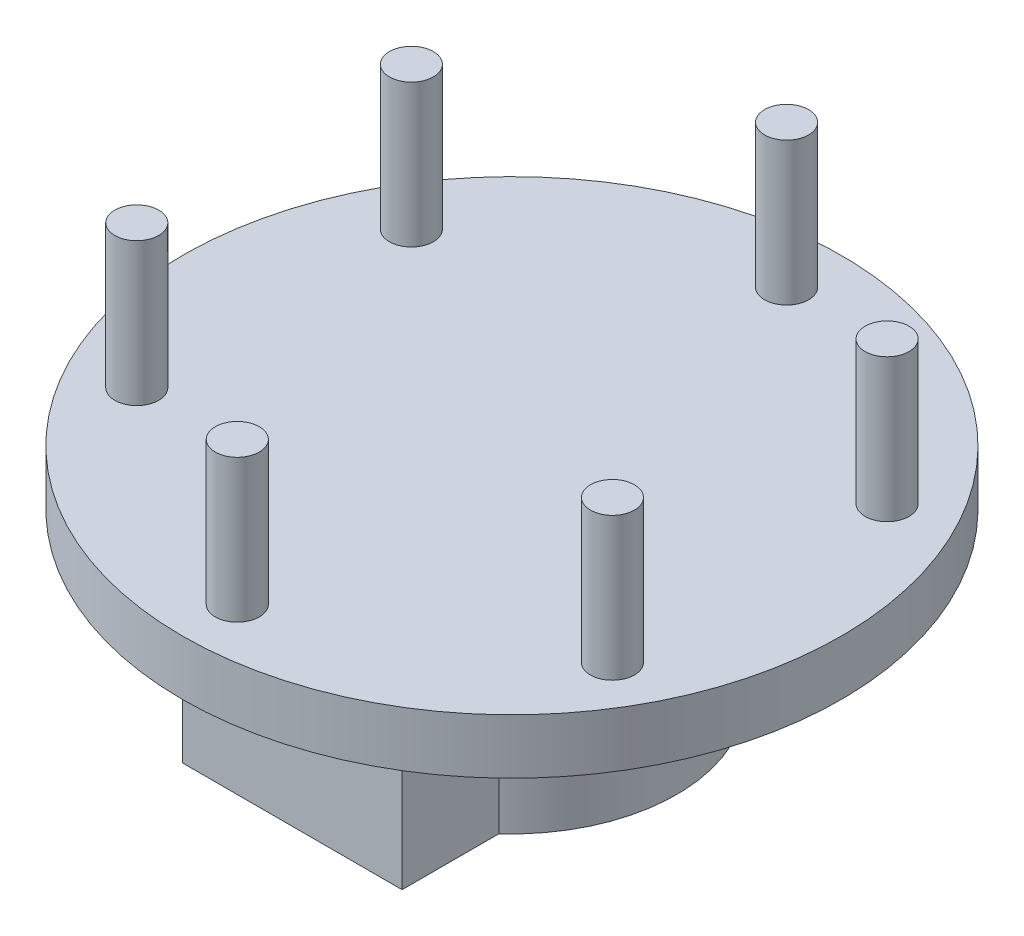
SolidWorks part; units mm, degrees
ref_plane "Front Plane" through (0, 0, 0) normal (0, 0, 1) x (1, 0, 0)
ref_plane "Top Plane" through (0, 0, 0) normal (0, 1, 0) x (1, 0, 0)
ref_plane "Right Plane" through (0, 0, 0) normal (1, 0, 0) x (0, 0, -1)
sketch "Sketch1" plane through (0, 0, 0) normal (0, 1, 0) x (1, 0, 0)
  circle A0 centre (0, 0) radius 30
  dimension "D1" = 60
extrude "Boss-Extrude1" add sketch "Sketch1" along normal blind 5
sketch "Sketch2" plane through (0, 5, 0) normal (0, 1, 0) x (1, 0, 0)
  circle A0 centre (0, 0) radius 25 construction
  circle A1 centre (0, 25) radius 2
  circle A2 centre (21.6506, 12.5) radius 2
  circle A3 centre (21.6506, -12.5) radius 2
  circle A4 centre (0, -25) radius 2
  circle A5 centre (-21.6506, -12.5) radius 2
  circle A6 centre (-21.6506, 12.5) radius 2
  point P17 (0, 0)
  dimension "D1" = 50
  dimension "D2" = 4
  dimension "D3" = 6
extrude "Boss-Extrude2" add sketch "Sketch2" along normal blind 13
sketch "Sketch3" plane through (0, 0, 0) normal (0, -1, 0) x (1, 0, 0)
  line L0 (0, 0) -> (0, 20) construction
  line L5 (-14.1893, 14.1017) -> (10.6394, -10.5737) construction
  line L6 (-10.3912, -13.8686) -> (10.8086, 14.4257) construction
  line L7 (-10, 20) -> (10, 20)
  line L8 (-10, 20) -> (-10, 11.1803)
  line L9 (10, 20) -> (10, 11.1803)
  arc A1 (-10, 11.1803) -> (10, 11.1803) centre (0, 0) ccw
  point P0 (0, 0)
  point P13 (0, 20)
  dimension "D1" = 25
  dimension "D2" = 25
  dimension "D4" = 30
  dimension "D3" = 20
  dimension "D5" = 20
extrude "Boss-Extrude3" add sketch "Sketch3" along normal blind 15
